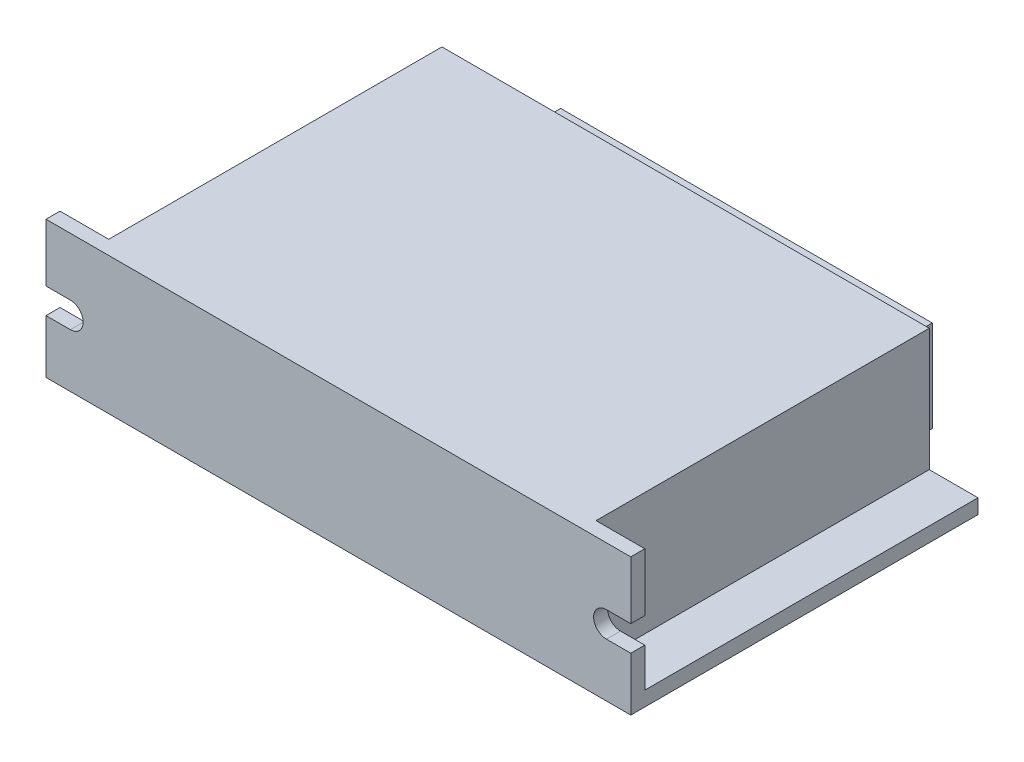
SolidWorks part; units mm, degrees
material "电源线路板"
ref_plane "前视基准面" through (0, 0, 0) normal (0, 0, 1) x (1, 0, 0)
ref_plane "上视基准面" through (0, 0, 0) normal (0, 1, 0) x (1, 0, 0)
ref_plane "右视基准面" through (0, 0, 0) normal (1, 0, 0) x (0, 0, -1)
sketch "草图1" plane through (0, 0, 0) normal (0, 1, 0) x (1, 0, 0)
  line L1 (-48, -28.5) -> (48, -28.5)
  line L2 (-48, -28.5) -> (-48, 28.5)
  line L3 (-48, 28.5) -> (48, 28.5)
  line L4 (48, -28.5) -> (48, 28.5)
  line L5 (-48, -28.5) -> (48, 28.5) construction
  line L6 (-48, 28.5) -> (48, -28.5) construction
  point P0 (0, 0)
  dimension "D1" = 96
  dimension "D2" = 57
extrude "凸台-拉伸1" add sketch "草图1" along normal blind 22.5
sketch "草图2" plane through (0, 0, -28.5) normal (0, 0, -1) x (-1, 0, 0)
  line L0 (-48, 0) -> (48, 0) construction
  line L1 (-30.5, 13.5) -> (30.5, 13.5)
  line L2 (-30.5, 13.5) -> (-30.5, -1.5)
  line L3 (-30.5, -1.5) -> (30.5, -1.5)
  line L4 (30.5, 13.5) -> (30.5, -1.5)
  line L5 (-30.5, 13.5) -> (30.5, -1.5) construction
  line L6 (-30.5, -1.5) -> (30.5, 13.5) construction
  point P0 (0, 6)
  dimension "D1" = 15
  dimension "D2" = 1.5
  dimension "D3" = 61
  dimension "D4" = 30.5
extrude "凸台-拉伸2" add sketch "草图2" along normal blind 10
sketch "草图3" plane through (0, 22.5, 0) normal (0, 1, 0) x (1, 0, 0)
  line L1 (48, 28.5) -> (40, 28.5)
  line L2 (48, 28.5) -> (48, -26.2)
  line L3 (48, -26.2) -> (40, -26.2)
  line L4 (40, 28.5) -> (40, -26.2)
  dimension "D1" = 54.7
  dimension "D2" = 8
extrude "切除-拉伸1" cut sketch "草图3" against normal blind 20.1
sketch "草图4" plane through (0, 0, 26.2) normal (0, 0, -1) x (-1, 0, 0)
  line L0 (-40, 22.5) -> (-48, 22.5) construction
  line L1 (-48, 2.4) -> (-48, 22.5) construction
  line L2 (-44, 8.8) -> (-48, 8.8)
  line L3 (-44, 13) -> (-48, 13)
  line L4 (-48, 8.8) -> (-48, 13)
  arc A0 (-44, 8.8) -> (-44, 13) centre (-44, 10.9) ccw
  dimension "D1" = 4.2
  dimension "D2" = 11.6
  dimension "D3" = 4
extrude "切除-拉伸2" cut sketch "草图4" against normal through all
mirror "镜向2" about plane through (0, 0, 0) normal (1, 0, 0) of "切除-拉伸1", "切除-拉伸2"
